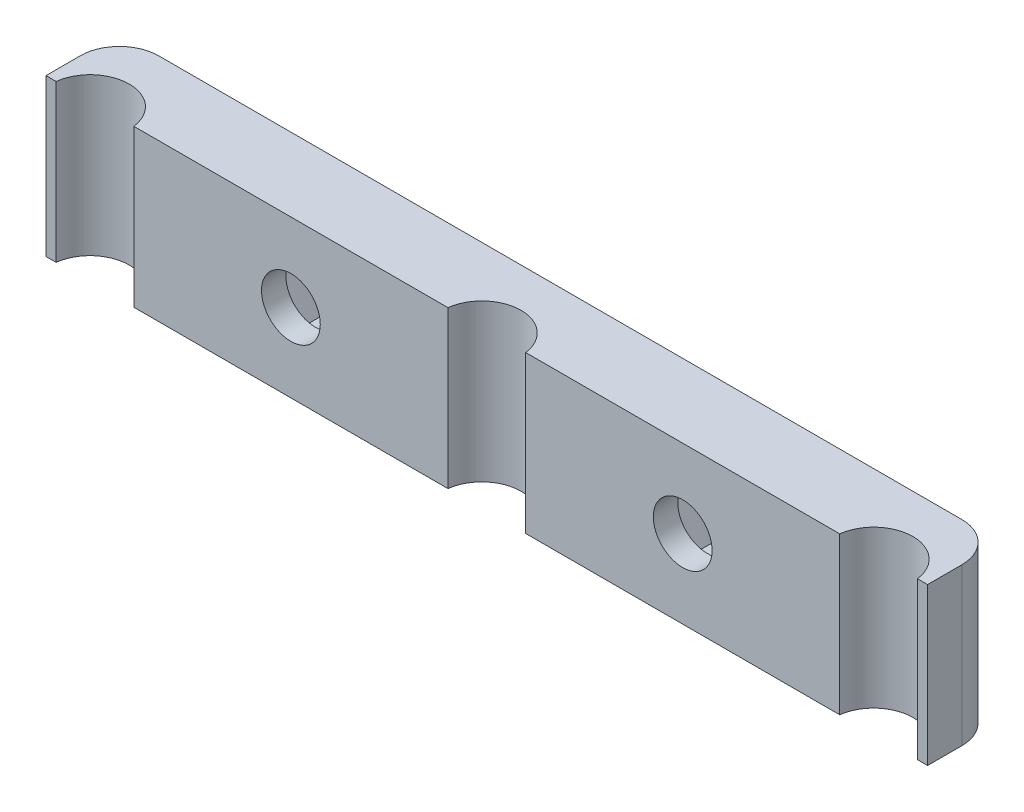
SolidWorks part; units mm, degrees
ref_plane "Plan de face" through (0, 0, 0) normal (0, 0, 1) x (1, 0, 0)
ref_plane "Plan de dessus" through (0, 0, 0) normal (0, 1, 0) x (1, 0, 0)
ref_plane "Plan de droite" through (0, 0, 0) normal (1, 0, 0) x (0, 0, -1)
sketch "Esquisse1" plane through (0, 0, 0) normal (0, 1, 0) x (1, 0, 0)
  line L0 (0, 0) -> (0, 4) construction
  line L1 (22.5, 4) -> (-22.5, 4)
  line L2 (-22.5, 4) -> (-22.5, 0.25)
  line L3 (-22.5, 0.25) -> (-21.9843, 0.25)
  line L4 (-18.0157, 0.25) -> (-1.9843, 0.25)
  line L5 (18.0157, 0.25) -> (1.9843, 0.25)
  line L6 (22.5, 0.25) -> (21.9843, 0.25)
  line L7 (22.5, 4) -> (22.5, 0.25)
  arc A0 (-18.0157, 0.25) -> (-21.9843, 0.25) centre (-20, 0) ccw
  arc A1 (1.9843, 0.25) -> (-1.9843, 0.25) centre (0, 0) ccw
  arc A2 (18.0157, 0.25) -> (21.9843, 0.25) centre (20, 0) cw
  dimension "D1" = 2
  dimension "D3" = 2.5
  dimension "D5" = 20
  dimension "D2" = 0.25
  dimension "D4" = 4
extrude "Boss.-Extru.1" add sketch "Esquisse1" along normal mid plane 8
fillet "Congé1" radius 2 2 edges at (-22.5, 0, -4) (22.5, 0, -4)
sketch "Esquisse2" plane through (0, 0, -0.25) normal (0, 0, 1) x (1, 0, 0)
  line L0 (-18.0157, 4) -> (-1.9843, 4) construction
  line L1 (1.9843, 4) -> (18.0157, 4) construction
  circle A0 centre (-10, 0) radius 1.5
  circle A1 centre (10, 0) radius 1.5
  point P5 (-10, 4)
  point P10 (10, 4)
  dimension "D1" = 3
extrude "Enlèv. mat.-Extru.1" cut sketch "Esquisse2" against normal through all
sketch "Esquisse3" plane through (0, 0, -4) normal (0, 0, -1) x (-1, 0, 0)
  line L1 (-8.4123, 2.75) -> (-11.5877, 2.75)
  line L2 (-11.5877, 2.75) -> (-13.1754, 0)
  line L3 (-13.1754, 0) -> (-11.5877, -2.75)
  line L4 (-11.5877, -2.75) -> (-8.4123, -2.75)
  line L5 (-8.4123, -2.75) -> (-6.8246, 0)
  line L6 (-6.8246, 0) -> (-8.4123, 2.75)
  line L7 (11.5877, 2.75) -> (8.4123, 2.75)
  line L8 (8.4123, 2.75) -> (6.8246, 0)
  line L9 (6.8246, 0) -> (8.4123, -2.75)
  line L10 (8.4123, -2.75) -> (11.5877, -2.75)
  line L11 (11.5877, -2.75) -> (13.1754, 0)
  line L12 (13.1754, 0) -> (11.5877, 2.75)
  circle A0 centre (-10, 0) radius 2.75 construction
  circle A1 centre (10, 0) radius 2.75 construction
  dimension "D1" = 5.5
extrude "Enlèv. mat.-Extru.2" cut sketch "Esquisse3" against normal blind 2.5
